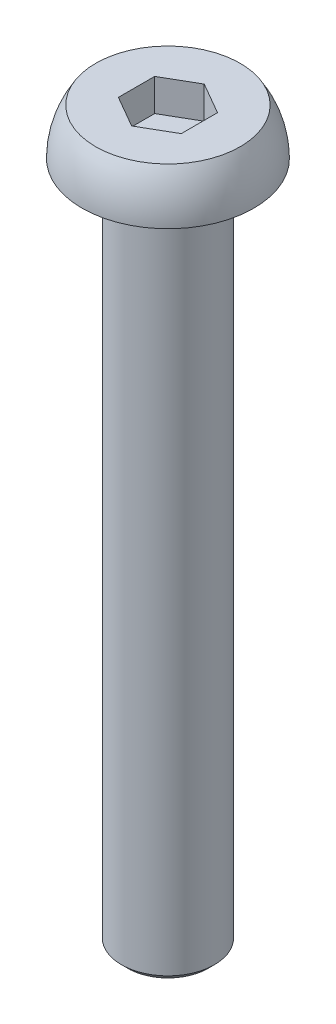
SolidWorks part; units mm, degrees
material "AISI 304"
ref_plane "前视基准面" through (0, 0, 0) normal (0, 0, 1) x (1, 0, 0)
ref_plane "上视基准面" through (0, 0, 0) normal (0, 1, 0) x (1, 0, 0)
ref_plane "右视基准面" through (0, 0, 0) normal (1, 0, 0) x (0, 0, -1)
sketch "草图1" plane through (0, 0, 0) normal (0, 0, 1) x (1, 0, 0)
  line L0 (0, 5.1118) -> (0, 0) construction
  line L1 (0, 0) -> (-2.775, 0)
  line L2 (-2.3347, 1.5) -> (0, 1.5)
  line L3 (0, 1.5) -> (0, 0)
  arc A1 (-2.3347, 1.5) -> (-2.775, 0) centre (0, 0) ccw
  dimension "D2" = 5.55
  dimension "D1" = 1.5
revolve "旋转1" add sketch "草图1" angle 360 about L0
sketch "草图2" plane through (0, 0, 0) normal (0, -1, 0) x (1, 0, 0)
  circle A0 centre (0, 0) radius 1.5
  dimension "D1" = 3
extrude "凸台-拉伸1" add sketch "草图2" along normal blind 22
sketch "草图3" plane through (0, 1.5, 0) normal (0, 1, 0) x (1, 0, 0)
  line L0 (0, 1.172) -> (-1.015, 0.586)
  line L1 (-1.015, 0.586) -> (-1.015, -0.586)
  line L2 (-1.015, -0.586) -> (0, -1.172)
  line L3 (0, -1.172) -> (1.015, -0.586)
  line L4 (1.015, -0.586) -> (1.015, 0.586)
  line L5 (1.015, 0.586) -> (0, 1.172)
  dimension "D1" = 2.03
extrude "切除-拉伸1" cut sketch "草图3" against normal blind 1.04
chamfer "倒角1" distance 0.2 angle 45 1 edges at (0, -22, -1.5)
